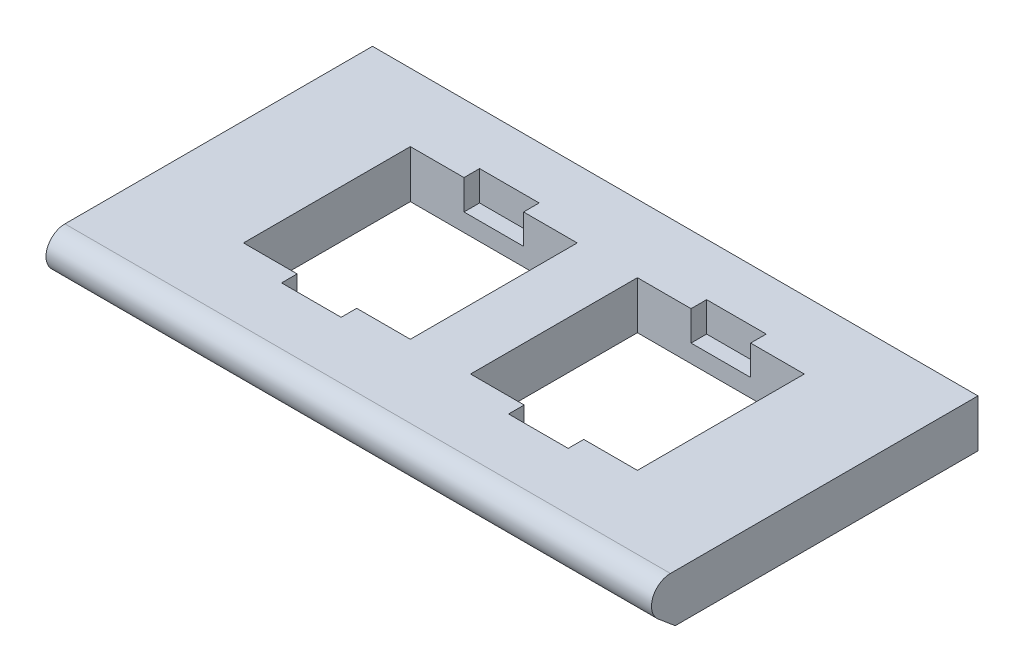
SolidWorks part; units mm, degrees
ref_plane "Front Plane" through (0, 0, 0) normal (0, 0, 1) x (1, 0, 0)
ref_plane "Top Plane" through (0, 0, 0) normal (0, 1, 0) x (1, 0, 0)
ref_plane "Right Plane" through (0, 0, 0) normal (1, 0, 0) x (0, 0, -1)
sketch "Sketch1" plane through (0, 0, 0) normal (0, 1, 0) x (1, 0, 0)
  line L1 (0, 0) -> (50.8, 0)
  line L2 (0, 0) -> (0, 25.4)
  line L3 (0, 25.4) -> (50.8, 25.4)
  line L4 (50.8, 0) -> (50.8, 25.4)
  dimension "D1" = 50.8
  dimension "D2" = 25.4
extrude "Boss-Extrude1" add sketch "Sketch1" along normal blind 4
sketch "Sketch2" plane through (0, 4, 0) normal (0, 1, 0) x (1, 0, 0)
  line L0 (22.8755, 12.7) -> (27.9245, 12.7) construction
  line L1 (8.8755, 19.7) -> (22.8755, 19.7)
  line L2 (8.8755, 19.7) -> (8.8755, 5.7)
  line L3 (8.8755, 5.7) -> (22.8755, 5.7)
  line L4 (22.8755, 19.7) -> (22.8755, 5.7)
  line L5 (27.9245, 19.7) -> (41.9245, 19.7)
  line L6 (27.9245, 19.7) -> (27.9245, 5.7)
  line L7 (27.9245, 5.7) -> (41.9245, 5.7)
  line L8 (41.9245, 19.7) -> (41.9245, 5.7)
  line L9 (50.8, 25.4) -> (0, 25.4) construction
  line L10 (50.8, 0) -> (50.8, 25.4) construction
  point P12 (25.4, 25.4)
  point P13 (25.4, 12.7)
  point P14 (0, 0)
  point P15 (30.1161, 14.0736)
  point P16 (27.8604, 12.7919)
  point P19 (50.8, 12.7)
  dimension "D1" = 14
  dimension "D2" = 14
  dimension "D3" = 5.049
extrude "Cut-Extrude1" cut sketch "Sketch2" against normal through all both and the other way through all
sketch "Sketch3" plane through (0, 4, 0) normal (0, 1, 0) x (1, 0, 0)
  line L0 (8.8755, 19.7) -> (22.8755, 19.7) construction
  line L1 (13.376, 19.7) -> (18.375, 19.7)
  line L2 (13.376, 19.7) -> (13.376, 21.0071)
  line L3 (13.376, 21.0071) -> (18.375, 21.0071)
  line L4 (18.375, 19.7) -> (18.375, 21.0071)
  line L5 (8.8755, 12.7) -> (41.9245, 12.7) construction
  line L6 (8.8755, 5.7) -> (8.8755, 19.7) construction
  line L7 (41.9245, 19.7) -> (41.9245, 5.7) construction
  line L8 (25.4, 25.4) -> (25.4, 0) construction
  line L9 (50.8, 25.4) -> (0, 25.4) construction
  line L10 (0, 0) -> (50.8, 0) construction
  line L11 (37.424, 21.0071) -> (32.425, 21.0071)
  line L12 (32.425, 19.7) -> (32.425, 21.0071)
  line L13 (37.424, 19.7) -> (32.425, 19.7)
  line L14 (37.424, 19.7) -> (37.424, 21.0071)
  line L15 (37.424, 5.7) -> (37.424, 4.3929)
  line L16 (37.424, 5.7) -> (32.425, 5.7)
  line L17 (32.425, 5.7) -> (32.425, 4.3929)
  line L18 (37.424, 4.3929) -> (32.425, 4.3929)
  line L19 (13.376, 4.3929) -> (18.375, 4.3929)
  line L20 (18.375, 5.7) -> (18.375, 4.3929)
  line L21 (13.376, 5.7) -> (18.375, 5.7)
  line L22 (13.376, 5.7) -> (13.376, 4.3929)
  point P6 (15.8755, 19.7)
  point P7 (15.8755, 21.0071)
  dimension "D1" = 4.999
  dimension "D2" = 1.3071
extrude "Cut-Extrude2" cut sketch "Sketch3" against normal blind 2.5001
sketch "Sketch5" plane through (0, 0, 0) normal (-1, 0, 0) x (0, 0, 1)
  line L0 (0, 0) -> (4.767, 4)
  line L1 (4.767, 4) -> (0, 4)
  line L2 (0, 4) -> (0, 0)
  line L3 (-25.4, 4) -> (0, 4) construction
  line L4 (-25.4, 0) -> (0, 0) construction
  dimension "D1" = 40
extrude "Boss-Extrude2" add sketch "Sketch5" against normal up to surface (50.8 mm away) up to face at (50.8, 2, -12.7)
fillet "Fillet1" radius 1.5875 1 edges at (25.4, 4, 4.767)
equation "\"D2@Sketch2\"=\"D1@Sketch2\""
